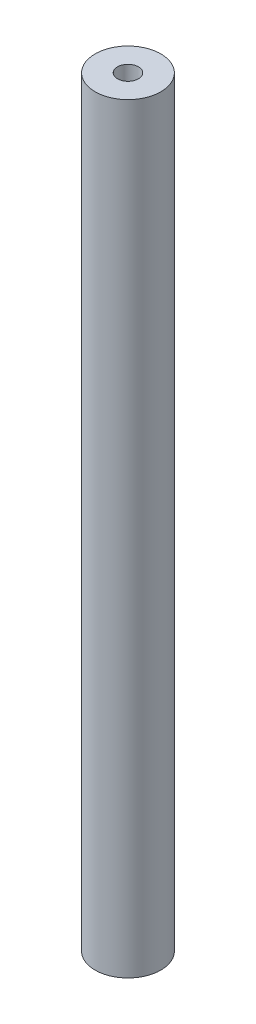
SolidWorks part; units mm, degrees
material "6061 Alloy"
ref_plane "Front Plane" through (0, 0, 0) normal (0, 0, 1) x (1, 0, 0)
ref_plane "Top Plane" through (0, 0, 0) normal (0, 1, 0) x (1, 0, 0)
ref_plane "Right Plane" through (0, 0, 0) normal (1, 0, 0) x (0, 0, -1)
sketch "Sketch1" plane through (0, 0, 0) normal (0, 1, 0) x (1, 0, 0)
  circle A0 centre (0, 0) radius 6.35
  dimension "D1" = 12.7
extrude "Boss-Extrude1" add sketch "Sketch1" along normal mid plane 147.066
hole_wizard "#10-32 Tapped Hole1" positions "Sketch3" profile "Sketch2" tap size "#10-32" standard "Ansi Inch"
sketch "Sketch3" plane through (0, 73.533, 0) normal (0, 1, 0) x (-1, 0, 0)
  point P0 (0, 0)
sketch "Sketch2" plane through (0, 73.533, 0) normal (1, 0, 0) x (0, 0, 1)
  line L0 (0, 0) -> (0, 13.1513)
  line L1 (0, 13.1513) -> (2.0193, 11.938)
  line L2 (2.0193, 11.938) -> (2.0193, 0)
  line L5 (2.0193, 0) -> (0, 0)
  line L10 (0, 13.1513) -> (-2.0193, 11.938) construction
  line L11 (0, -6.35) -> (0, 107.95) construction
  dimension "Tap Drill Dia." = 4.0386
  dimension "Tap Drill Depth" = 11.938
  dimension "Drill Angle" = 118
mirror "Mirror1" about plane through (0, 0, 0) normal (0, 1, 0) of "#10-32 Tapped Hole1"
